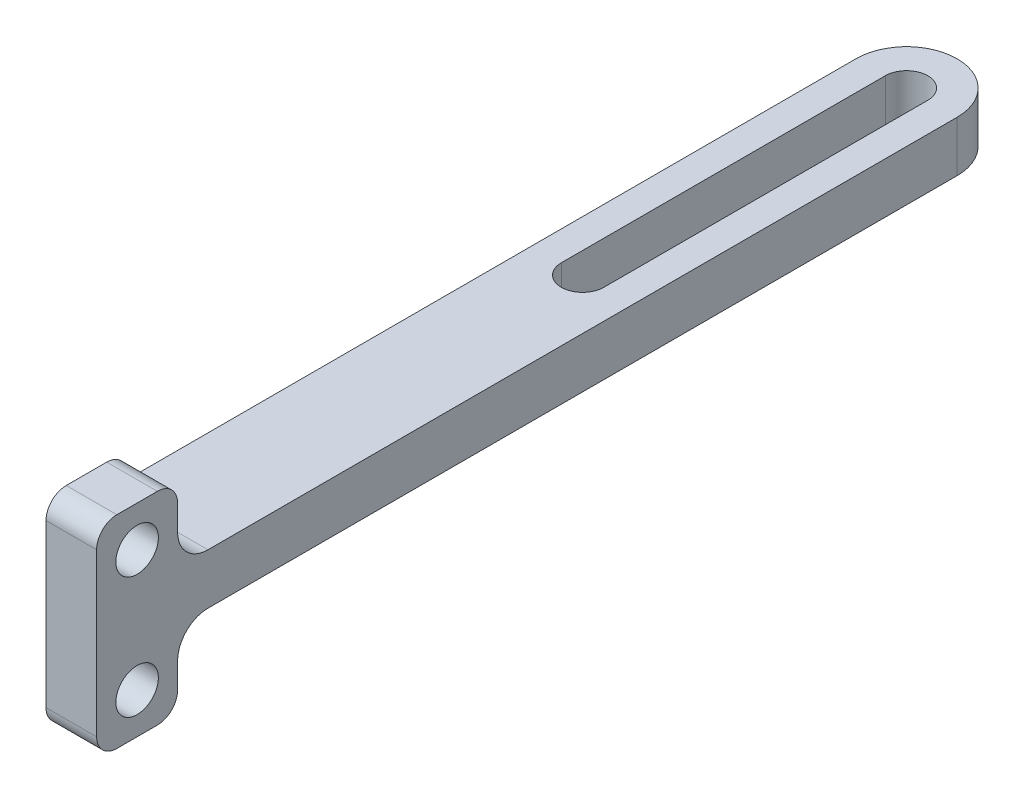
SolidWorks part; units mm, degrees
ref_plane "Front" through (0, 0, 0) normal (0, 0, 1) x (1, 0, 0)
ref_plane "Top" through (0, 0, 0) normal (0, 1, 0) x (1, 0, 0)
ref_plane "Right" through (0, 0, 0) normal (1, 0, 0) x (0, 0, -1)
sketch "Sketch1" plane through (0, 0, 0) normal (0, 1, 0) x (1, 0, 0)
  line L0 (0, 32) -> (0, 0) construction
  line L1 (0, 32) -> (0, 0) construction
  line L2 (2.1, 32) -> (2.1, 0)
  line L3 (-2.1, 32) -> (-2.1, 0)
  line L4 (5, 32) -> (5, 0)
  line L5 (-5, 32) -> (-5, 0)
  line L6 (-5, 0) -> (-5, -45)
  line L7 (-5, -45) -> (5, -45)
  line L8 (5, -45) -> (5, 0)
  arc A0 (2.1, 32) -> (-2.1, 32) centre (0, 32) ccw
  arc A1 (-2.1, 0) -> (2.1, 0) centre (0, 0) ccw
  arc A2 (5, 32) -> (-5, 32) centre (0, 32) ccw
  point P3 (0, 16)
  point P10 (0, 16)
extrude "Boss-Extrude1" add sketch "Sketch1" along normal blind 5
sketch "Sketch2" plane through (0, 0, 45) normal (0, 0, 1) x (1, 0, 0)
  line L1 (0, 12.5) -> (0, -7.5)
  line L6 (0, -7.5) -> (5, -7.5)
  line L12 (0, 12.5) -> (5, 12.5)
  line L13 (5, -7.5) -> (5, 12.5)
  point P4 (0, 2.5)
  point P7 (0, 2.5)
  point P9 (5, 2.5)
extrude "Boss-Extrude2" add sketch "Sketch2" along normal blind 8
sketch "Sketch3" plane through (5, 0, 0) normal (1, 0, 0) x (0, 0, -1)
  circle A0 centre (-49, 8.5) radius 2.1
  circle A1 centre (-49, -3.5) radius 2.1
extrude "Cut-Extrude1" cut sketch "Sketch3" against normal blind 8
fillet "Fillet2" radius 2 4 edges at (2.5, -7.5, 45) (2.5, -7.5, 53) (2.5, 12.5, 45) (2.5, 12.5, 53)
sketch "Sketch4" plane through (0, 0, 45) normal (0, 0, 1) x (1, 0, 0)
  line L1 (-5, 5) -> (0, 5)
  line L2 (-5, 5) -> (-5, 0)
  line L3 (-5, 0) -> (0, 0)
  line L4 (0, 5) -> (0, 0)
extrude "Cut-Extrude2" cut sketch "Sketch4" against normal blind 3
fillet "Fillet3" radius 3 3 edges at (2.5, 0, 45) (-5, 2.5, 42) (2.5, 5, 45)
